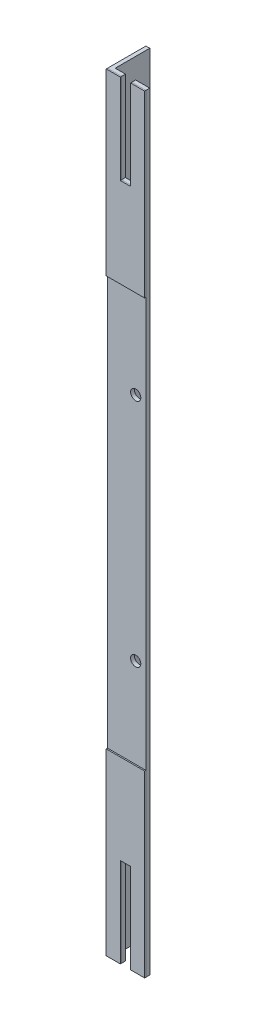
SolidWorks part; units mm, degrees
material "Alliage 1060"
ref_plane "Plan de face" through (0, 0, 0) normal (0, 0, 1) x (1, 0, 0)
ref_plane "Plan de dessus" through (0, 0, 0) normal (0, 1, 0) x (1, 0, 0)
ref_plane "Plan de droite" through (0, 0, 0) normal (1, 0, 0) x (0, 0, -1)
sketch "Esquisse1" plane through (0, 0, 0) normal (0, 1, 0) x (1, 0, 0)
  line L0 (0, 30) -> (0, 0)
  line L1 (0, 0) -> (30, 0)
  dimension "D1" = 30
extrude "Extru.-Mince1" add sketch "Esquisse1" along normal mid plane 600 thin thin type one direction reverse wall 3
sketch "Esquisse2" plane through (0, 0, 0) normal (0, 0, 1) x (1, 0, 0)
  line L0 (0, 300) -> (30, 300) construction
  line L1 (11, 300) -> (19, 300)
  line L2 (11, 300) -> (11, 230)
  line L3 (11, 230) -> (19, 230)
  line L4 (19, 300) -> (19, 230)
  line L5 (0, 0) -> (30, 0) construction
  line L6 (30, 300) -> (30, -300) construction
  line L7 (19, -300) -> (19, -230)
  line L8 (11, -230) -> (19, -230)
  line L9 (11, -300) -> (11, -230)
  line L10 (11, -300) -> (19, -300)
  line L11 (0, 300) -> (0, -300) construction
  circle A0 centre (22, 90) radius 4
  circle A1 centre (22, -90) radius 4
  dimension "D1" = 8
  dimension "D3" = 8
  dimension "D7" = 8
  dimension "D2" = 11
  dimension "D4" = 70
  dimension "D5" = 11
  dimension "D6" = 210
extrude "Enlèv. mat.-Extru.1" cut sketch "Esquisse2" against normal through all
sketch "Esquisse3" plane through (0, 0, 0) normal (0, 0, 1) x (1, 0, 0)
  line L0 (0, 160) -> (30, 160)
  line L1 (0, -160) -> (0, -300)
  line L2 (30, -160) -> (0, -160)
  line L3 (30, 160) -> (30, 300)
  line L14 (0, -300) -> (11, -300)
  line L15 (11, -300) -> (11, -230)
  line L16 (11, -230) -> (19, -230)
  line L17 (19, -230) -> (19, -300)
  line L18 (19, -300) -> (30, -300)
  line L19 (30, -300) -> (30, 300)
  line L20 (30, 300) -> (19, 300)
  line L21 (19, 300) -> (19, 230)
  line L22 (19, 230) -> (11, 230)
  line L23 (11, 230) -> (11, 300)
  line L24 (11, 300) -> (0, 300)
  line L25 (0, 300) -> (0, -300)
  line L26 (0, -300) -> (11, -300)
  line L27 (11, -300) -> (11, -230)
  line L28 (11, -230) -> (19, -230)
  line L29 (19, -230) -> (19, -300)
  line L30 (19, -300) -> (30, -300)
  line L31 (30, -300) -> (30, -160)
  line L32 (30, 300) -> (19, 300)
  line L33 (19, 300) -> (19, 230)
  line L34 (19, 230) -> (11, 230)
  line L35 (11, 230) -> (11, 300)
  line L36 (11, 300) -> (0, 300)
  line L37 (0, 300) -> (0, 160)
  dimension "D1" = 0
  dimension "D2" = 140
extrude "Boss.-Extru.1" add sketch "Esquisse3" along normal blind 1 separate body
